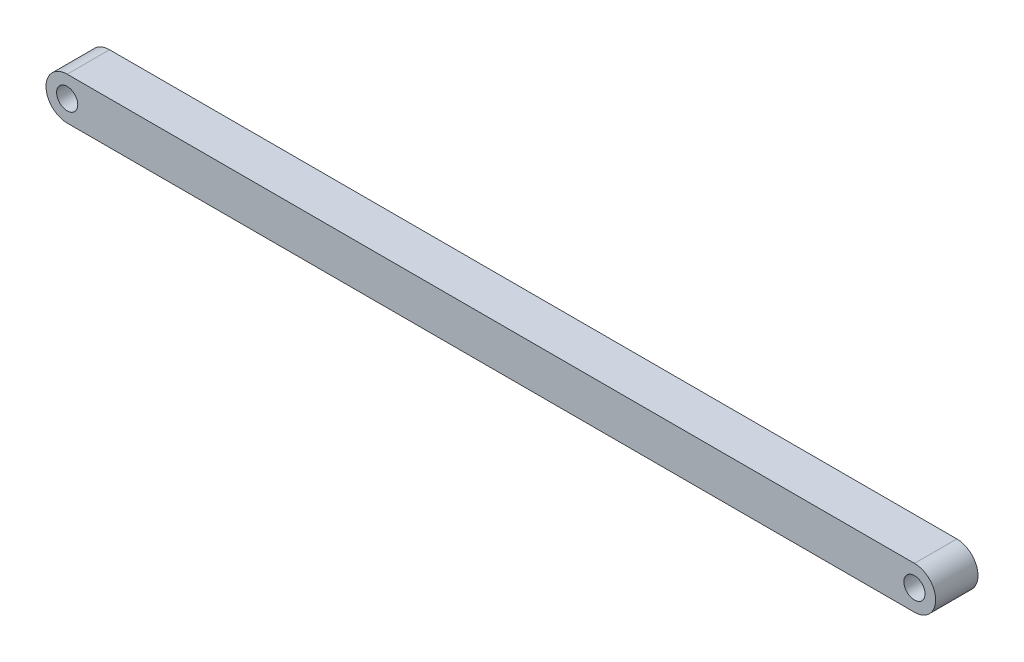
SolidWorks part; units mm, degrees
ref_plane "Front Plane" through (0, 0, 0) normal (0, 0, 1) x (1, 0, 0)
ref_plane "Top Plane" through (0, 0, 0) normal (0, 1, 0) x (1, 0, 0)
ref_plane "Right Plane" through (0, 0, 0) normal (1, 0, 0) x (0, 0, -1)
sketch "Sketch1" plane through (0, 0, 0) normal (0, 0, 1) x (1, 0, 0)
  line L0 (-50, 0) -> (50, 0) construction
  line L3 (-50, 2.5) -> (50, 2.5)
  line L4 (-50, -2.5) -> (50, -2.5)
  arc A2 (-50, 2.5) -> (-50, -2.5) centre (-50, 0) ccw
  arc A3 (50, -2.5) -> (50, 2.5) centre (50, 0) ccw
  circle A4 centre (-50, 0) radius 1.25
  circle A5 centre (50, 0) radius 1.25
  point P3 (0, 0)
  dimension "D1" = 2.5
  dimension "D2" = 2.5
  dimension "D3" = 5
  dimension "D4" = 100
extrude "Boss-Extrude1" add sketch "Sketch1" along normal blind 5
